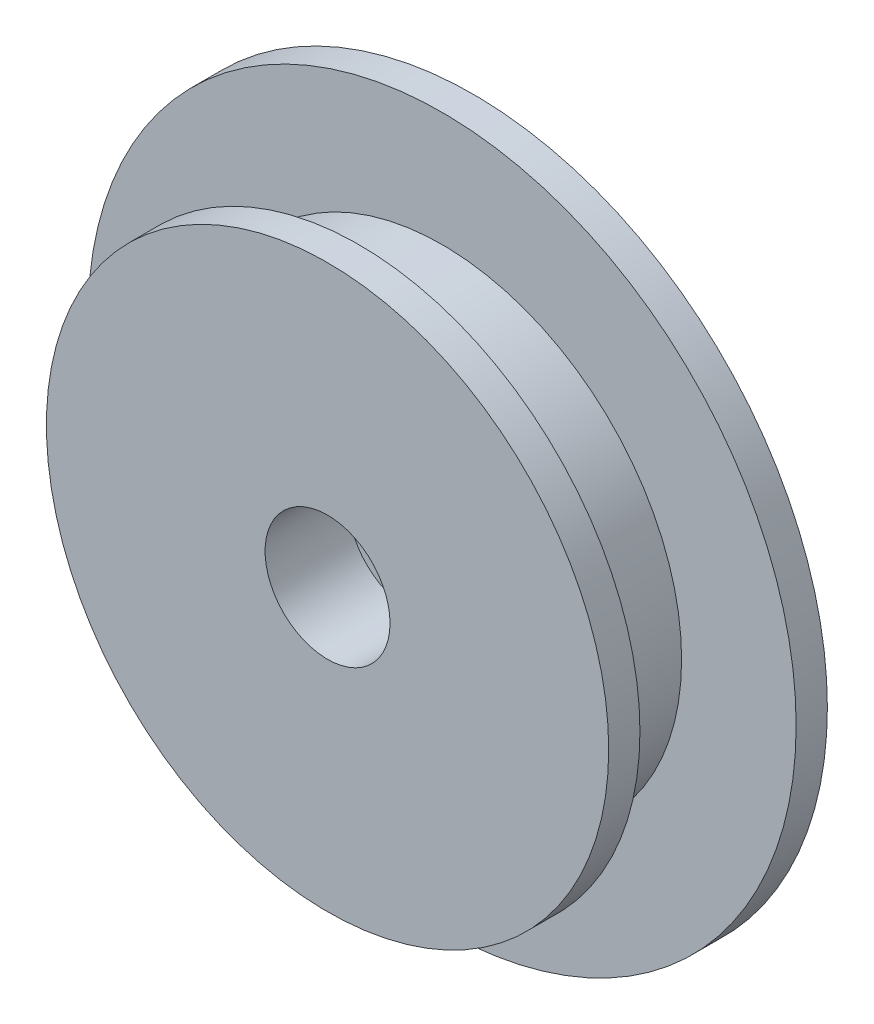
SolidWorks part; units mm, degrees
ref_plane "前视基准面" through (0, 0, 0) normal (0, 0, 1) x (1, 0, 0)
ref_plane "上视基准面" through (0, 0, 0) normal (0, 1, 0) x (1, 0, 0)
ref_plane "右视基准面" through (0, 0, 0) normal (1, 0, 0) x (0, 0, -1)
sketch "草图2" plane through (0, 0, 0) normal (0, 0, 1) x (1, 0, 0)
  circle A0 centre (0, 0) radius 17
  dimension "D1" = 34
extrude "凸台-拉伸1" add sketch "草图2" along normal blind 1.5
sketch "草图3" plane through (0, 0, 1.5) normal (0, 0, 1) x (1, 0, 0)
  circle A0 centre (0, 0) radius 11.5
  dimension "D1" = 23
extrude "凸台-拉伸2" add sketch "草图3" along normal blind 4
sketch "草图4" plane through (0, 0, 5.5) normal (0, 0, 1) x (1, 0, 0)
  circle A0 centre (0, 0) radius 13.5
  dimension "D1" = 27
extrude "凸台-拉伸3" add sketch "草图4" along normal blind 1.5
sketch "草图5" plane through (0, 0, 7) normal (0, 0, 1) x (1, 0, 0)
  circle A0 centre (0, 0) radius 1.75
  dimension "D1" = 3.5
extrude "切除-拉伸1" cut sketch "草图5" against normal through all
sketch "草图6" plane through (0, 0, 7) normal (0, 0, 1) x (1, 0, 0)
  circle A0 centre (0, 0) radius 3
  dimension "D1" = 6
extrude "切除-拉伸2" cut sketch "草图6" against normal blind 4
